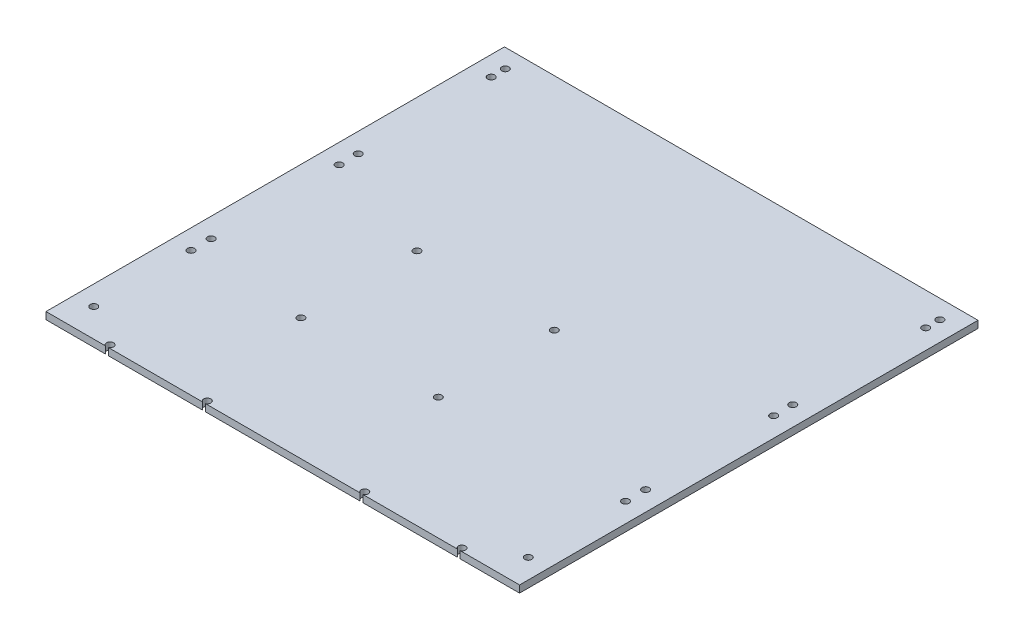
SolidWorks part; units mm, degrees
material "PMMA"
ref_plane "前视基准面" through (0, 0, 0) normal (0, 0, 1) x (1, 0, 0)
ref_plane "上视基准面" through (0, 0, 0) normal (0, 1, 0) x (1, 0, 0)
ref_plane "右视基准面" through (0, 0, 0) normal (1, 0, 0) x (0, 0, -1)
sketch "草图1" plane through (0, 0, 0) normal (0, 1, 0) x (1, 0, 0)
  line L1 (-100, 70) -> (100, 70)
  line L2 (-100, 70) -> (-100, -70)
  line L3 (-100, -70) -> (100, -70)
  line L4 (100, 70) -> (100, -70)
  line L5 (-100, 70) -> (100, -70) construction
  line L6 (-100, -70) -> (100, 70) construction
  point P0 (0, 0)
  dimension "D1" = 200
  dimension "D2" = 140
extrude "凸台-拉伸1" add sketch "草图1" along normal blind 3
sketch "草图2" plane through (0, 0, 0) normal (0, -1, 0) x (1, 0, 0)
  line L0 (100, -70) -> (-100, -70) construction
  line L1 (-80, -70) -> (-80, 60.2109)
  line L2 (-80, 60.2109) -> (80, 60.2109)
  line L3 (-80, -70) -> (80, -70)
  line L4 (80, 60.2109) -> (80, -70)
  line L5 (0, -2.3222) -> (0, -107.1787) construction
  line L6 (-100, 0) -> (60.0254, 0) construction
  line L7 (-100, -70) -> (-100, 70) construction
  circle A0 centre (91.7562, -62.1301) radius 1.5
  circle A1 centre (-91.7562, -62.1301) radius 1.5
  circle A2 centre (91.7562, 62.1301) radius 1.5
  circle A3 centre (-91.7562, 62.1301) radius 1.5
  circle A4 centre (-91.7562, 0) radius 1.5
  circle A5 centre (91.7562, 0) radius 1.5
  dimension "D1" = 3
extrude "切除-拉伸1" cut sketch "草图2" against normal blind 6
sketch "草图3" plane through (0, 3, 0) normal (0, 1, 0) x (1, 0, 0)
  line L0 (81.9415, -129.3049) -> (81.9415, -67.5441) construction
  line L1 (100, -70) -> (81.9415, -70)
  line L2 (100, -70) -> (100, -123.6149)
  line L3 (100, -123.6149) -> (81.9415, -123.6149)
  line L4 (81.9415, -70) -> (81.9415, -123.6149)
  line L5 (0, -72.2422) -> (0, -100.0691) construction
  line L6 (-100, -123.6149) -> (-81.9415, -123.6149)
  line L7 (-100, -70) -> (-100, -123.6149)
  line L8 (-100, -70) -> (-81.9415, -70)
  line L9 (-81.9415, -70) -> (-81.9415, -123.6149)
extrude "凸台-拉伸2" add sketch "草图3" against normal blind 3
sketch "草图4" plane through (0, 3, 0) normal (0, 1, 0) x (1, 0, 0)
  line L0 (-91.7562, -62.1301) -> (-91.7562, -111.6916) construction
  line L1 (0, 0) -> (0, -89.9452) construction
  circle A0 centre (-91.7562, -111.6916) radius 1.5
  circle A1 centre (91.7562, -111.6916) radius 1.5
  dimension "D1" = 3
extrude "切除-拉伸2" cut sketch "草图4" against normal blind 3
sketch "草图5" plane through (0, 0, 60.2109) normal (0, 0, -1) x (-1, 0, 0)
  line L0 (-80, 3) -> (-80, 0) construction
  line L1 (-80, 3) -> (80, 3)
  line L2 (-80, 3) -> (-80, 0)
  line L3 (-80, 0) -> (80, 0)
  line L4 (80, 3) -> (80, 0)
  line L5 (80, 0) -> (100, 0) construction
  line L6 (-80, 0) -> (80, 0) construction
extrude "凸台-拉伸3" add sketch "草图5" along normal up to surface (130.2109 mm away) up to face at (-90, 1.5, -70)
sketch "草图6" plane through (0, 0, 70) normal (0, 0, 1) x (1, 0, 0)
  line L1 (-81.9415, 3) -> (81.9415, 3)
  line L2 (-81.9415, 3) -> (-81.9415, 0)
  line L3 (-81.9415, 0) -> (81.9415, 0)
  line L4 (81.9415, 3) -> (81.9415, 0)
extrude "凸台-拉伸5" add sketch "草图6" along normal up to surface (53.6149 mm away) up to face at (90.9708, 1.5, 123.6149)
sketch "草图7" plane through (0, 3, 0) normal (0, 1, 0) x (1, 0, 0)
  circle A0 centre (-74.308, -122.2503) radius 1.5
  circle A1 centre (-33.25, -122.2503) radius 1.5
  circle A2 centre (33.25, -122.2503) radius 1.5
  circle A3 centre (74.308, -122.2503) radius 1.5
extrude "切除-拉伸3" cut sketch "草图7" against normal blind 5
sketch "草图8" plane through (0, 3, 0) normal (0, 1, 0) x (1, 0, 0)
  circle A0 centre (14.1445, -23.0835) radius 1.5
  circle A1 centre (-43.8555, -23.0835) radius 1.5
  circle A2 centre (-43.8555, -72.0835) radius 1.5
  circle A3 centre (14.1445, -72.0835) radius 1.5
extrude "切除-拉伸4" cut sketch "草图8" against normal blind 3
sketch "草图9" plane through (0, 3, 0) normal (0, 1, 0) x (1, 0, 0)
  line L0 (0, 75.1669) -> (0, 60.4853) construction
  circle A0 centre (-91.7562, -70.6252) radius 1.5
  circle A1 centre (-91.7562, -8.0604) radius 1.5
  circle A2 centre (-91.7562, 56.1634) radius 1.5
  circle A3 centre (91.7562, 56.1634) radius 1.5
  circle A4 centre (91.7562, -8.0604) radius 1.5
  circle A5 centre (91.7562, -70.6252) radius 1.5
extrude "切除-拉伸5" cut sketch "草图9" against normal blind 3
